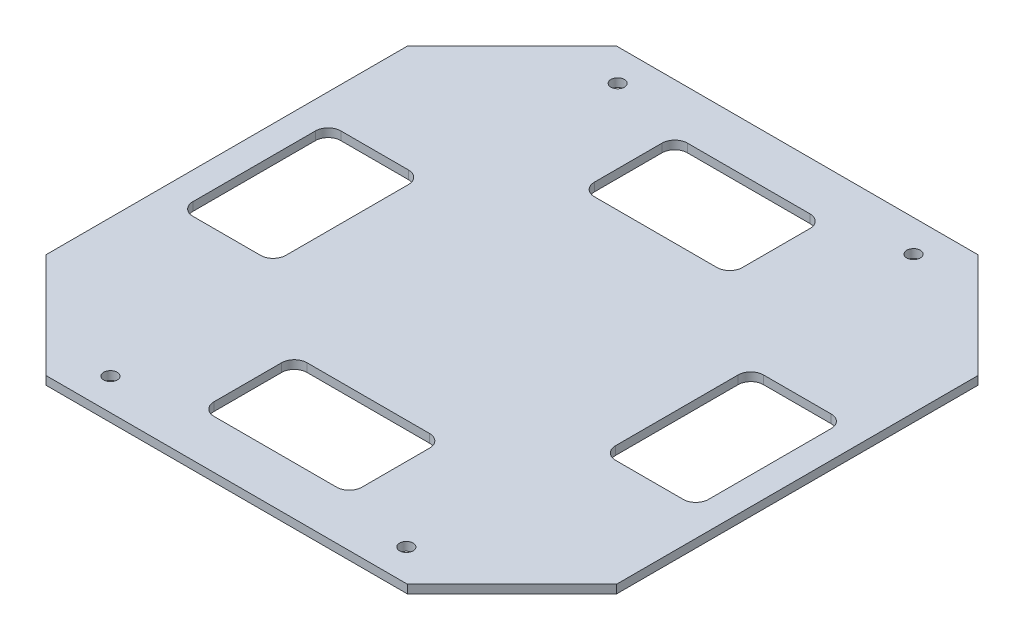
SolidWorks part; units mm, degrees
material "Thornel Mat VMA"
ref_plane "Front Plane" through (0, 0, 0) normal (0, 0, 1) x (1, 0, 0)
ref_plane "Top Plane" through (0, 0, 0) normal (0, 1, 0) x (1, 0, 0)
ref_plane "Right Plane" through (0, 0, 0) normal (1, 0, 0) x (0, 0, -1)
sketch "Sketch1" plane through (0, 0, 0) normal (0, 1, 0) x (1, 0, 0)
  line L0 (-42.7513, 67.5) -> (-67.5, 42.7513)
  line L1 (-42.7513, 67.5) -> (42.7513, 67.5)
  line L2 (-67.5, 42.7513) -> (-67.5, -42.7513)
  line L3 (-42.7513, -67.5) -> (42.7513, -67.5)
  line L4 (67.5, 42.7513) -> (67.5, -42.7513)
  line L5 (-55.1256, 55.1256) -> (55.1256, -55.1256) construction
  line L6 (-55.1256, -55.1256) -> (55.1256, 55.1256) construction
  line L7 (67.5, -42.7513) -> (42.7513, -67.5)
  line L8 (42.7513, 67.5) -> (67.5, 42.7513)
  line L9 (-67.5, -42.7513) -> (-42.7513, -67.5)
  point P0 (0, 0)
  point P9 (-55.1256, 55.1256)
  point P12 (55.1256, -55.1256)
  point P16 (55.1256, 55.1256)
  point P18 (-55.1256, -55.1256)
  dimension "D1" = 135
  dimension "D2" = 35
  dimension "D3" = 35
  dimension "D4" = 35
  dimension "D5" = 35
  dimension "D6" = 135
extrude "Boss-Extrude1" add sketch "Sketch1" along normal blind 2
hole_wizard "M3 Clearance Hole1" positions "Sketch2" profile "Sketch3" hole size "M3" standard "ANSI Metric" end condition through all
sketch "Sketch2" plane through (0, 2, 0) normal (0, 1, 0) x (1, 0, 0)
  line L1 (35, -60) -> (-35, -60)
  line L2 (35, -60) -> (35, 60)
  line L3 (35, 60) -> (-35, 60)
  line L4 (-35, -60) -> (-35, 60)
  line L5 (35, -60) -> (-35, 60) construction
  line L6 (35, 60) -> (-35, -60) construction
  point P4 (-35, 60)
  point P47 (35, -60)
  point P48 (35, 60)
  point P49 (-35, -60)
  point P61 (0, 0)
  point P62 (0, 0)
  point P63 (10.7338, 0)
  point P64 (0, 0)
  point P66 (0, 0)
  point P67 (7.5388, -11.9354)
  point P68 (0, 0)
  dimension "D1" = 70
  dimension "D2" = 120
sketch "Sketch3" plane through (-35, 2, -60) normal (1, 0, 0) x (0, 0, 1)
  line L0 (0, 0) -> (0, 2)
  line L1 (0, 2) -> (1.6, 2)
  line L2 (1.6, 2) -> (1.6, 0)
  line L5 (1.6, 0) -> (0, 0)
  line L11 (0, -6.35) -> (0, 107.95) construction
  dimension "Thru Hole Dia." = 3.2
  dimension "Thru Hole Depth" = 2
sketch "Sketch4" plane through (0, 2, 0) normal (0, 1, 0) x (1, 0, 0)
  line L0 (0, 67.5) -> (0, -67.5) construction
  line L1 (42.7513, 67.5) -> (-42.7513, 67.5) construction
  line L2 (-42.7513, -67.5) -> (42.7513, -67.5) construction
  line L3 (-67.5, 0) -> (67.5, 0) construction
  line L4 (-67.5, 42.7513) -> (-67.5, -42.7513) construction
  line L5 (67.5, -42.7513) -> (67.5, 42.7513) construction
  line L7 (17.5, 34) -> (-17.5, 34)
  line L8 (17.5, 34) -> (17.5, 56)
  line L9 (17.5, 56) -> (-17.5, 56)
  line L10 (-17.5, 34) -> (-17.5, 56)
  line L11 (17.5, 34) -> (-17.5, 56) construction
  line L12 (17.5, 56) -> (-17.5, 34) construction
  line L13 (-61, 17.5) -> (-39, 17.5)
  line L14 (-61, 17.5) -> (-61, -17.5)
  line L15 (-61, -17.5) -> (-39, -17.5)
  line L16 (-39, 17.5) -> (-39, -17.5)
  line L17 (-61, 17.5) -> (-39, -17.5) construction
  line L18 (-61, -17.5) -> (-39, 17.5) construction
  line L19 (39, 17.5) -> (61, 17.5)
  line L20 (39, 17.5) -> (39, -17.5)
  line L21 (39, -17.5) -> (61, -17.5)
  line L22 (61, 17.5) -> (61, -17.5)
  line L23 (39, 17.5) -> (61, -17.5) construction
  line L24 (39, -17.5) -> (61, 17.5) construction
  line L25 (-17.5, -56) -> (17.5, -56)
  line L26 (-17.5, -56) -> (-17.5, -34)
  line L27 (-17.5, -34) -> (17.5, -34)
  line L28 (17.5, -56) -> (17.5, -34)
  line L29 (-17.5, -56) -> (17.5, -34) construction
  line L30 (-17.5, -34) -> (17.5, -56) construction
  point P12 (0, 45)
  point P17 (-50, 0)
  point P22 (50, 0)
  point P27 (0, -45)
  dimension "D1" = 22
  dimension "D2" = 35
  dimension "D3" = 45
  dimension "D4" = 35
  dimension "D5" = 22
  dimension "D6" = 50
  dimension "D7" = 22
  dimension "D8" = 35
  dimension "D9" = 50
  dimension "D10" = 35
  dimension "D11" = 22
  dimension "D12" = 45
extrude "Cut-Extrude1" cut sketch "Sketch4" against normal through all
fillet "Fillet1" radius 3 16 edges at (17.5, 1, 56) (-17.5, 1, 56) (-17.5, 1, 34) (17.5, 1, 34) (61, 1, 17.5) (39, 1, 17.5) (39, 1, -17.5) (61, 1, -17.5) (-39, 1, 17.5) (-61, 1, 17.5) (-61, 1, -17.5) (-39, 1, -17.5) (17.5, 1, -56) (17.5, 1, -34) (-17.5, 1, -34) (-17.5, 1, -56)
